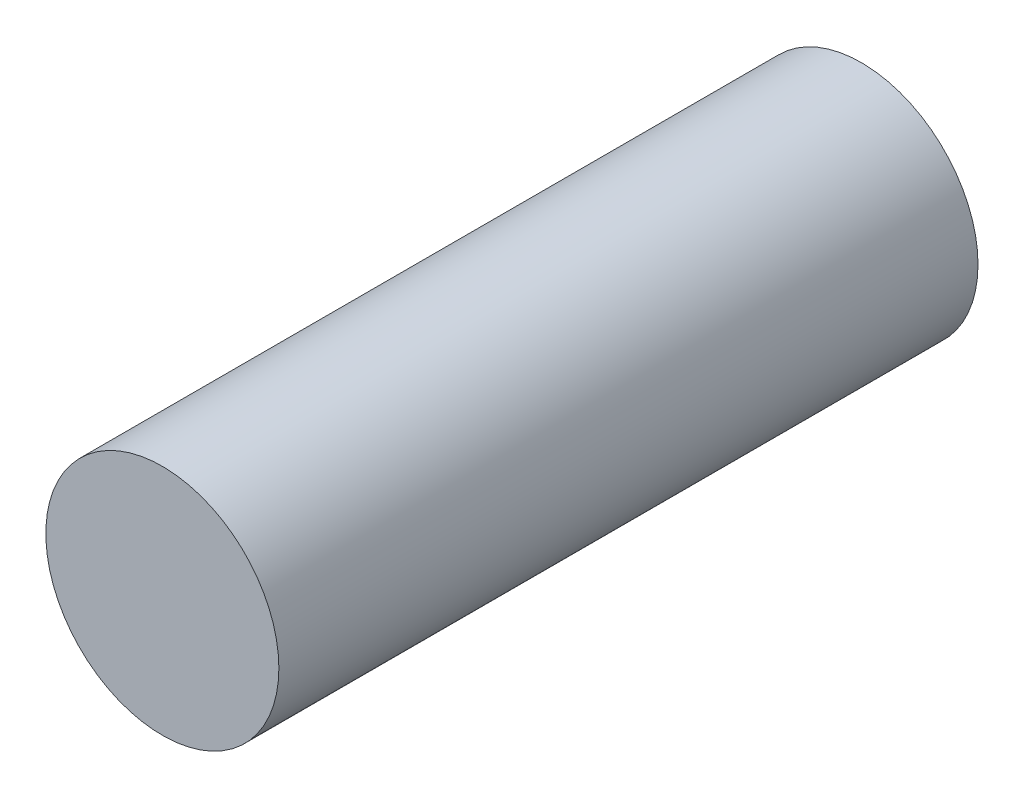
SolidWorks part; units mm, degrees
ref_plane "前视基准面" through (0, 0, 0) normal (0, 0, 1) x (1, 0, 0)
ref_plane "上视基准面" through (0, 0, 0) normal (0, 1, 0) x (1, 0, 0)
ref_plane "右视基准面" through (0, 0, 0) normal (1, 0, 0) x (0, 0, -1)
sketch "草图1" plane through (0, 0, 0) normal (0, 0, 1) x (1, 0, 0)
  circle A0 centre (-42.5017, -93.7828) radius 5
extrude "凸台-拉伸1" add sketch "草图1" against normal up to surface (30 mm away)
